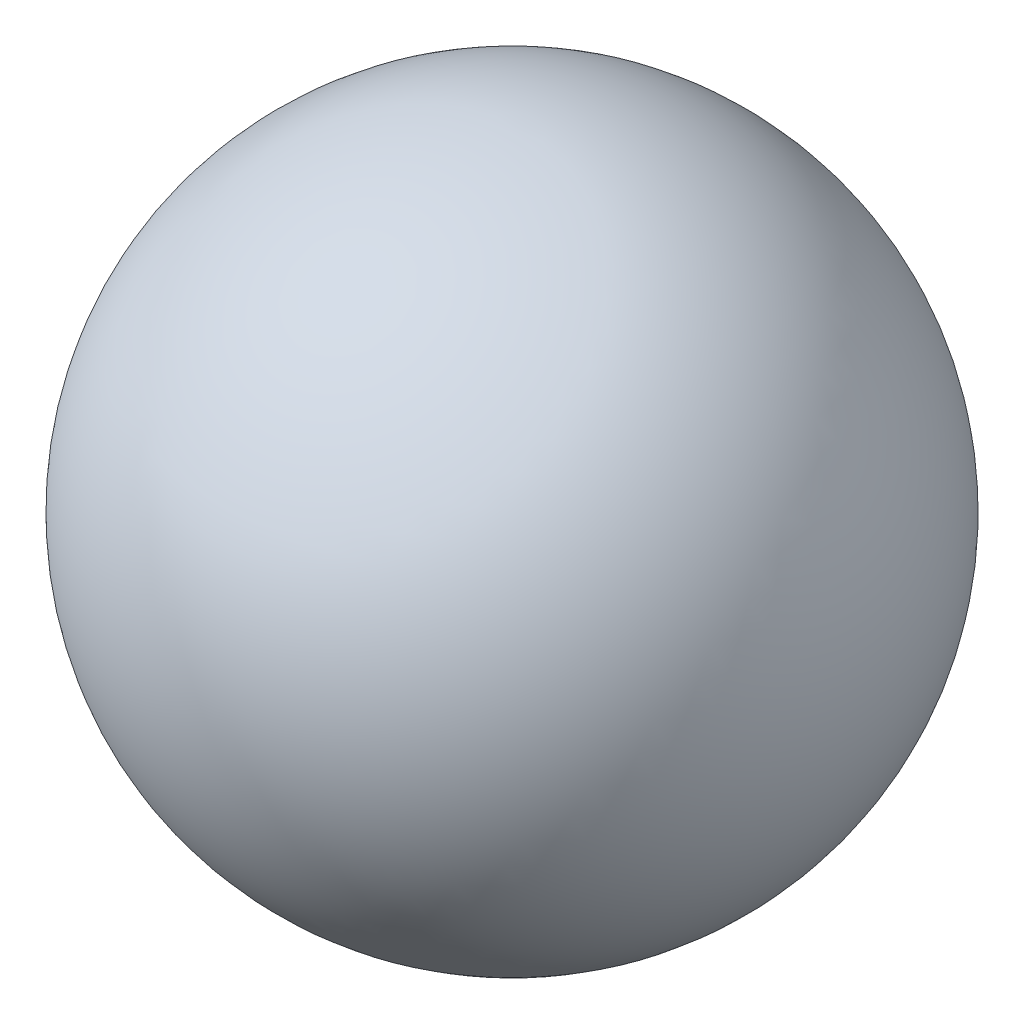
SolidWorks part; units mm, degrees
ref_plane "Front Plane" through (0, 0, 0) normal (0, 0, 1) x (1, 0, 0)
ref_plane "Top Plane" through (0, 0, 0) normal (0, 1, 0) x (1, 0, 0)
ref_plane "Right Plane" through (0, 0, 0) normal (1, 0, 0) x (0, 0, -1)
sketch "Sketch2" plane through (0, 0, 0) normal (0, 0, 1) x (1, 0, 0)
  line L0 (0, 20) -> (0, -20)
  arc A0 (0, -20) -> (0, 20) centre (0, 0) ccw
  dimension "D1" = 40
revolve "Revolve1" add sketch "Sketch2" angle 360 about L0
sketch "Sketch3" plane through (0, 0, 0) normal (0, 0, 1) x (1, 0, 0)
  line L0 (-8.7178, -18) -> (8.7178, -18)
  circle A0 centre (0, 0) radius 20 construction
  dimension "D1" = 18
extrude "Cut-Extrude1" cut sketch "Sketch3" against normal through all both and the other way through all flip side to cut
hole_wizard "M10 Tapped Hole1" positions "Sketch4" profile "Sketch5" tap size "M10" standard "ISO"
sketch "Sketch4" plane through (0, -18, 0) normal (0, -1, 0) x (-1, 0, 0)
  point P0 (0, 0)
sketch "Sketch5" plane through (0, -18, 0) normal (1, 0, 0) x (0, 0, -1)
  line L0 (0, 0) -> (0, 12.5537)
  line L1 (0, 12.5537) -> (4.25, 10)
  line L2 (4.25, 10) -> (4.25, 0)
  line L5 (4.25, 0) -> (0, 0)
  line L10 (0, 12.5537) -> (-4.25, 10) construction
  line L11 (0, -6.35) -> (0, 107.95) construction
  dimension "Tap Drill Dia." = 8.5
  dimension "Tap Drill Depth" = 10
  dimension "Drill Angle" = 118
cosmetic thread "Hole Thread1" parameters "D1"=9, "D2"=10
